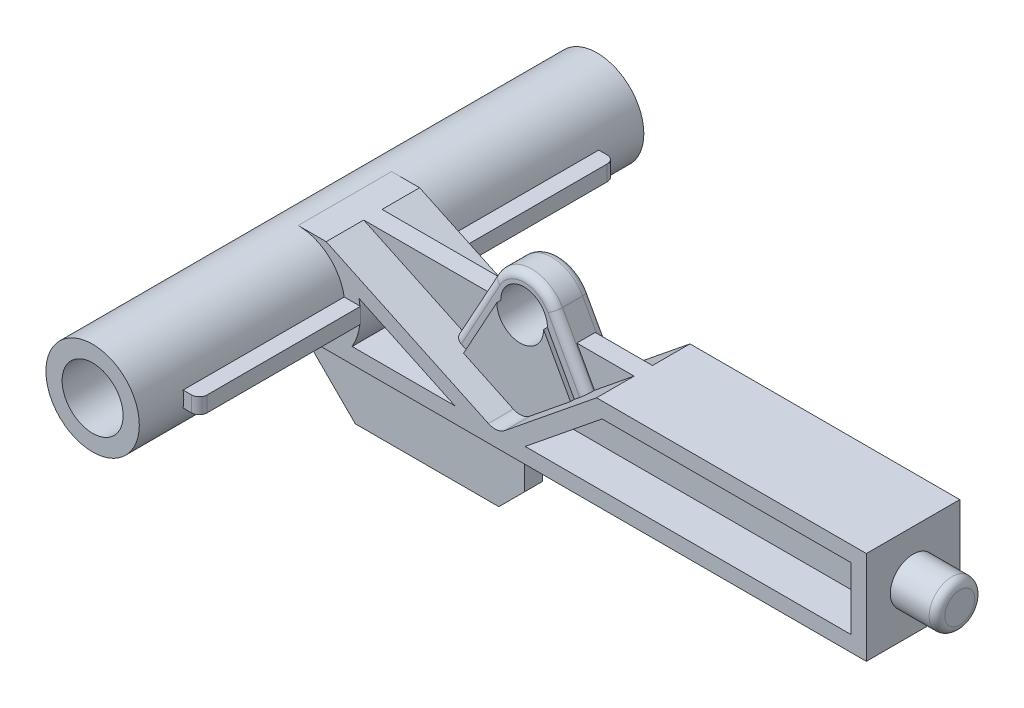
SolidWorks part; units mm, degrees
ref_plane "Front Plane" through (0, 0, 0) normal (0, 0, 1) x (1, 0, 0)
ref_plane "Top Plane" through (0, 0, 0) normal (0, 1, 0) x (1, 0, 0)
ref_plane "Right Plane" through (0, 0, 0) normal (1, 0, 0) x (0, 0, -1)
sketch "Sketch1" plane through (0, 0, 0) normal (0, 0, 1) x (1, 0, 0)
  line L0 (0, 0) -> (36.5, 0)
  line L1 (36.5, 0) -> (36.5, 6)
  line L2 (36.5, 6) -> (20.75, 6)
  line L3 (20.75, 6) -> (11.75, 6) construction
  line L4 (20.75, 6) -> (20.75, 2) construction
  line L5 (20.75, 2) -> (11.75, 2) construction
  line L6 (11.75, 2) -> (11.75, 6) construction
  line L7 (16.75, 10) -> (16.75, 2) construction
  line L8 (12.75, 6) -> (20.75, 6) construction
  line L9 (15.5737, 2.9411) -> (11.75, 6)
  line L10 (11.75, 6) -> (0, 6)
  line L11 (0, 6) -> (0, 0) construction
  arc A1 (20.75, 6) -> (19.541, 3.1347) centre (16.75, 6) cw
  arc A2 (15.5737, 2.9411) -> (19.541, 3.1347) centre (17.4478, 5.2837) ccw
  circle A4 centre (0, 3) radius 3
  dimension "D4" = 3
  dimension "D1" = 36.5
  dimension "D2" = 6
  dimension "D3" = 15.75
  dimension "D5" = 4
  dimension "D6" = 9
extrude "Boss-Extrude3" add sketch "Sketch1" along normal mid plane 6 contours A4 L0 L1 L2 A1 A2 L9 L10
sketch "Sketch2" plane through (0, 0, 0) normal (0, 0, 1) x (1, 0, 0)
  circle A0 centre (0, 3) radius 3
extrude "Boss-Extrude4" add sketch "Sketch2" along normal mid plane 32.41
sketch "Sketch5" plane through (0, 0, 16.205) normal (0, 0, 1) x (1, 0, 0)
  circle A0 centre (0, 3) radius 1.96
  dimension "D1" = 3.92
extrude "Cut-Extrude2" cut sketch "Sketch5" against normal blind 32.8
sketch "Sketch6" plane through (36.5, 0, 0) normal (1, 0, 0) x (0, 0, -1)
  circle A0 centre (0, 3) radius 1.465
  dimension "D1" = 2.93
extrude "Boss-Extrude7" add sketch "Sketch6" along normal blind 3 contours A0
fillet "Fillet1" radius 0.5 1 edges at (39.5, 3, -1.465)
sketch "Sketch12" plane through (0, 0, 0) normal (0, 0, 1) x (1, 0, 0)
  line L0 (36.5, 0) -> (12.12, 0) construction
  line L1 (0, 0) -> (36.5, 0) construction
  line L2 (12.12, 0) -> (12.12, -3.97)
  line L3 (12.12, -3.97) -> (10.4795, -5.6105)
  line L4 (10.4795, -5.6105) -> (1.2595, -5.6105)
  line L5 (1.2595, -5.6105) -> (-2.8064, -1.5446)
  line L6 (-2.8064, -1.5446) -> (-2.8064, 1.9396)
  line L7 (12.12, 0) -> (0, 0)
  circle A0 centre (0, 3) radius 3 construction
  arc A1 (-2.8064, 1.9396) -> (0, 0) centre (0, 3) ccw
  dimension "D1" = 24.38
  dimension "D2" = 3.97
  dimension "D3" = 2.32
  dimension "D4" = 9.22
  dimension "D5" = 5.75
extrude "Boss-Extrude8" add sketch "Sketch12" along normal mid plane 1.18
sketch "Sketch14" plane through (0, 0, 0) normal (0, 0, 1) x (1, 0, 0)
  line L1 (4, 2.5) -> (4, 3.5)
  line L2 (4, 3.5) -> (2.958, 3.5)
  line L3 (4, 2.5) -> (2.958, 2.5)
  circle A0 centre (0, 3) radius 3 construction
  arc A2 (2.958, 3.5) -> (2.958, 2.5) centre (0, 3) cw
  point P6 (4, 3)
  dimension "D1" = 1
extrude "Boss-Extrude9" add sketch "Sketch14" along normal mid plane 26.7
fillet "Fillet7" radius 0.5 1 edges at (4, 3, 13.35)
fillet "Fillet8" radius 0.5 1 edges at (4, 3, -13.35)
sketch "Sketch15" plane through (0, 0, 0) normal (0, 0, 1) x (1, 0, 0)
  line L0 (5.875, 6) -> (27.0772, 6)
  line L1 (11.75, 6) -> (0, 6) construction
  line L2 (36.5, 6) -> (20.75, 6) construction
  line L3 (27.0772, 6) -> (27.0772, 1.4897)
  line L4 (27.0772, 1.4897) -> (5.875, 1.4897)
  line L5 (5.875, 1.4897) -> (5.875, 6)
extrude "Boss-Extrude10" add sketch "Sketch15" along normal mid plane 6
sketch "Sketch16" plane through (0, 0, 0) normal (0, 0, 1) x (1, 0, 0)
  line L0 (0, 6) -> (1.8, 6)
  line L1 (36.5, 6) -> (0, 6) construction
  line L2 (1.8, 6) -> (19.17, 6) construction
  line L3 (1.8, 6) -> (19.17, 6)
  line L5 (1.8, 6) -> (12.2149, 1.0953)
  line L6 (13.2702, 1.2228) -> (19.17, 6)
  arc A0 (13.2702, 1.2228) -> (12.2149, 1.0953) centre (12.6409, 2) cw
  dimension "D4" = 1
  dimension "D1" = 1.8
  dimension "D2" = 17.37
extrude "Cut-Extrude4" cut sketch "Sketch16" against normal mid plane 6 contours A0 L6 L3 L5
sketch "Sketch17" plane through (0, 0, 0) normal (0, 0, 1) x (1, 0, 0)
  line L0 (1.8, 6) -> (19.17, 6)
  line L1 (19.17, 6) -> (19.17, 0.4969)
  line L2 (19.17, 0.4969) -> (1.8, 0.4969)
  line L3 (1.8, 0.4969) -> (4.8905, 2.3962)
  line L4 (4.8905, 2.3962) -> (1.8, 6)
extrude "Boss-Extrude11" add sketch "Sketch17" along normal mid plane 1.18
sketch "Sketch19" plane through (0, 0, 0) normal (0, 0, 1) x (1, 0, 0)
  line L0 (12.6557, 1.0001) -> (12.6557, 11.1504) construction
  line L1 (12.6557, 6.0753) -> (12.6557, 8.6853)
  line L2 (1.8, 6) -> (8.17, 3.0002) construction
  line L3 (1.8, 6) -> (12.2149, 1.0953) construction
  line L4 (8.17, 3.0002) -> (10.6847, 7.5691)
  line L5 (14.6269, 7.5692) -> (15.4907, 6)
  line L6 (19.17, 6) -> (1.8, 6) construction
  line L7 (15.4907, 6) -> (16.625, 3.9393)
  line L8 (13.2702, 1.2228) -> (19.17, 6) construction
  line L9 (8.17, 3.0002) -> (12.2149, 1.0953)
  line L10 (16.625, 3.9393) -> (13.2702, 1.2228)
  arc A0 (12.2149, 1.0953) -> (13.2702, 1.2228) centre (12.6409, 2) ccw construction
  arc A1 (12.2149, 1.0953) -> (13.2702, 1.2228) centre (12.6409, 2) ccw construction
  arc A2 (12.2149, 1.0953) -> (13.2702, 1.2228) centre (12.6409, 2) ccw
  arc A3 (10.6847, 7.5691) -> (14.6269, 7.5692) centre (12.6558, 6.4842) cw
  dimension "D5" = 2.25
  dimension "D1" = 2.61
  dimension "D2" = 6.37
  dimension "D3" = 151.173
  dimension "D4" = 151.17
extrude "Boss-Extrude12" add sketch "Sketch19" along normal mid plane 2.79 contours A2 L10 L7 L5 A3 L4 L9
sketch "Sketch20" plane through (0, 0, 1.395) normal (0, 0, 1) x (1, 0, 0)
  line L0 (11.1558, 6.4842) -> (9.0184, 2.6006)
  line L1 (8.17, 3.0002) -> (12.2149, 1.0953) construction
  line L2 (8.17, 3.0002) -> (10.6847, 7.5691) construction
  line L3 (14.1558, 6.4842) -> (15.886, 3.3409)
  line L4 (16.625, 3.9393) -> (13.2702, 1.2228) construction
  line L5 (14.6269, 7.5692) -> (16.625, 3.9393) construction
  line L6 (8.17, 3.0002) -> (9.0184, 2.6006)
  line L7 (15.886, 3.3409) -> (16.625, 3.9393)
  line L8 (14.6269, 7.5692) -> (16.625, 3.9393)
  arc A2 (10.6847, 7.5691) -> (14.6269, 7.5692) centre (12.6558, 6.4842) cw
  arc A3 (11.1558, 6.4842) -> (14.1558, 6.4842) centre (12.6558, 6.4842) ccw
  circle A4 centre (12.6558, 6.4842) radius 1.5
  dimension "D1" = 3
extrude "Cut-Extrude6" cut sketch "Sketch20" against normal mid plane 41.79 contours A3 A4
sketch "Sketch21" plane through (0, 0, 1.395) normal (0, 0, 1) x (1, 0, 0)
  line L0 (11.1558, 6.4842) -> (9.0184, 2.6006)
  line L1 (1.8, 6) -> (12.2149, 1.0953) construction
  line L2 (8.17, 3.0002) -> (9.821, 6) construction
  line L3 (14.1558, 6.4842) -> (15.886, 3.3409)
  line L4 (16.625, 3.9393) -> (13.2702, 1.2228) construction
  line L5 (15.4907, 6) -> (16.625, 3.9393) construction
  line L6 (8.17, 3.0002) -> (9.0184, 2.6006)
  line L7 (16.625, 3.9393) -> (15.886, 3.3409)
  line L8 (10.6847, 7.5691) -> (8.17, 3.0002)
  line L9 (14.6269, 7.5692) -> (16.625, 3.9393)
  circle A0 centre (12.6558, 6.4842) radius 1.5 construction
  arc A1 (10.6847, 7.5691) -> (14.6269, 7.5692) centre (12.6558, 6.4842) cw
  arc A2 (11.1558, 6.4842) -> (14.1558, 6.4842) centre (12.6558, 6.4842) ccw
extrude "Cut-Extrude7" cut sketch "Sketch21" against normal mid plane 0.5
sketch "Sketch22" plane through (0, 0, -1.395) normal (0, 0, -1) x (-1, 0, 0)
  line L0 (-14.1558, 6.4842) -> (-15.886, 3.3409)
  line L1 (-13.2702, 1.2228) -> (-19.17, 6) construction
  line L2 (-15.4907, 6) -> (-16.625, 3.9393) construction
  line L3 (-11.1558, 6.4842) -> (-9.0184, 2.6006)
  line L4 (-8.17, 3.0002) -> (-12.2149, 1.0953) construction
  line L5 (-8.17, 3.0002) -> (-10.6847, 7.5691) construction
  line L6 (-16.625, 3.9393) -> (-15.886, 3.3409)
  line L7 (-8.17, 3.0002) -> (-9.0184, 2.6006)
  line L8 (-14.6269, 7.5692) -> (-16.625, 3.9393)
  line L9 (-10.6847, 7.5691) -> (-8.17, 3.0002)
  circle A0 centre (-12.6558, 6.4842) radius 1.5 construction
  arc A1 (-14.6269, 7.5692) -> (-10.6847, 7.5691) centre (-12.6558, 6.4842) cw
  arc A2 (-14.1558, 6.4842) -> (-11.1558, 6.4842) centre (-12.6558, 6.4842) ccw
extrude "Cut-Extrude8" cut sketch "Sketch22" against normal mid plane 0.5
fillet "Fillet9" radius 0.5 3 edges at (9.4273, 5.2846, -1.145) (15.626, 5.7542, -1.145) (12.6558, 8.7342, -1.145)
fillet "Fillet10" radius 0.5 3 edges at (15.626, 5.7542, 1.145) (9.4273, 5.2846, 1.145) (12.6558, 8.7342, 1.145)
sketch "Sketch23" plane through (0, 0, -3) normal (0, 0, -1) x (-1, 0, 0)
  line L0 (-35.5, 5) -> (-35.5, 1)
  line L1 (-35.5, 1) -> (-14.23, 1)
  line L2 (-36.5, 0) -> (-36.5, 6) construction
  line L5 (-35.5, 5) -> (-19.17, 5)
  line L6 (-36.5, 6) -> (-19.17, 6) construction
  line L7 (-19.17, 5) -> (-14.23, 1)
  line L8 (-15.886, 3.3409) -> (-13.2702, 1.2228) construction
  dimension "D1" = 1
  dimension "D3" = 1
extrude "Cut-Extrude9" cut sketch "Sketch23" against normal blind 2.5
sketch "Sketch24" plane through (0, 0, -3) normal (0, 0, -1) x (-1, 0, 0)
  line L0 (-10.0701, 1) -> (-3.4641, 1)
  line L1 (-3.8956, 3.9078) -> (-10.0701, 1)
  line L2 (-9.0184, 2.6006) -> (-12.2149, 1.0953) construction
  line L3 (-1.8, 6) -> (-12.2149, 1.0953) construction
  arc A0 (-3.4641, 1) -> (-3.8956, 3.9078) centre (0, 3) cw
  arc A1 (-2.958, 2.5) -> (0, 0) centre (0, 3) ccw construction
  dimension "D2" = 1
  dimension "D1" = 1
extrude "Cut-Extrude10" cut sketch "Sketch24" against normal blind 2.5
sketch "Sketch25" plane through (0, 0, 3) normal (0, 0, 1) x (1, 0, 0)
  line L2 (19.5241, 5) -> (35.5, 5)
  line L3 (35.5, 5) -> (35.5, 1)
  line L5 (36.5, 6) -> (19.17, 6) construction
  line L6 (36.5, 0) -> (36.5, 6) construction
  line L16 (35.5, 1) -> (14.5841, 1)
  line L17 (0, 0) -> (36.5, 0) construction
  line L18 (19.5241, 5) -> (14.5841, 1)
  dimension "D1" = 1
  dimension "D2" = 1
  dimension "D4" = 1
sketch "Sketch26" plane through (0, 0, 3) normal (0, 0, 1) x (1, 0, 0)
  line L0 (3.4641, 1) -> (10.0701, 1)
  line L1 (0, 0) -> (36.5, 0) construction
  line L2 (1.8, 6) -> (12.2149, 1.0953) construction
  line L3 (3.8956, 3.9078) -> (10.0701, 1)
  arc A0 (3.8956, 3.9078) -> (3.4641, 1) centre (0, 3) cw
  circle A1 centre (0, 3) radius 3 construction
  arc A2 (0, 0) -> (2.958, 2.5) centre (0, 3) ccw construction
  dimension "D1" = 1
  dimension "D6" = 1
  dimension "D2" = 1
  dimension "D3" = 1
  dimension "D4" = 1
extrude "Cut-Extrude12" cut sketch "Sketch25" against normal blind 2.5
extrude "Cut-Extrude14" cut sketch "Sketch26" against normal blind 2.5
